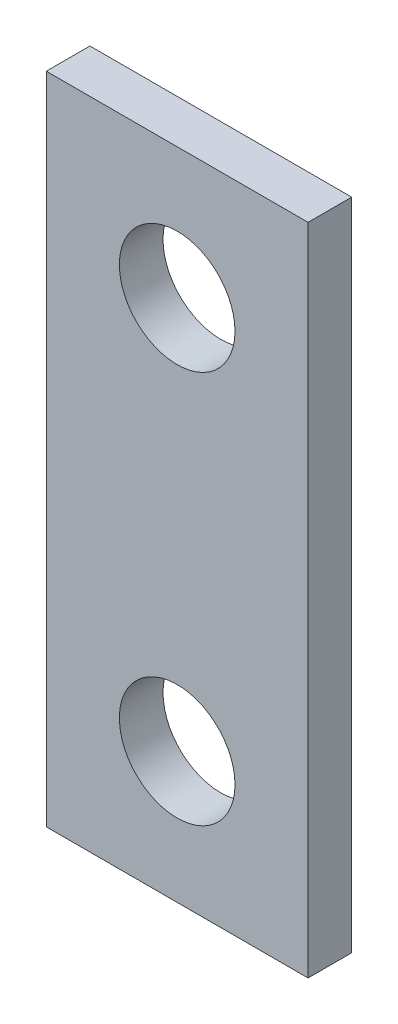
SolidWorks part; units mm, degrees
material "AISI 1045 钢，冷拔"
ref_plane "前视基准面" through (0, 0, 0) normal (0, 0, 1) x (1, 0, 0)
ref_plane "上视基准面" through (0, 0, 0) normal (0, 1, 0) x (1, 0, 0)
ref_plane "右视基准面" through (0, 0, 0) normal (1, 0, 0) x (0, 0, -1)
sketch "草图1" plane through (0, 0, 0) normal (0, 0, 1) x (1, 0, 0)
  line L1 (-6, -15) -> (6, -15)
  line L2 (-6, -15) -> (-6, 15)
  line L3 (-6, 15) -> (6, 15)
  line L4 (6, -15) -> (6, 15)
  line L5 (-6, -15) -> (6, 15) construction
  line L6 (-6, 15) -> (6, -15) construction
  point P0 (0, 0)
  dimension "D1" = 30
  dimension "D2" = 12
extrude "凸台-拉伸1" add sketch "草图1" along normal blind 2
hole_wizard "M5 间隙孔1" positions "草图3" profile "草图2" hole size "M5" standard "GB" end condition up to next
sketch "草图3" plane through (0, 0, 2) normal (0, 0, 1) x (1, 0, 0)
  line L0 (-6, -15) -> (6, -15) construction
  point P0 (0, -9)
  point P2 (0, 9)
  dimension "D1" = 18
  dimension "D2" = 6
sketch "草图2" plane through (0, -9, 2) normal (1, 0, 0) x (0, -1, 0)
  line L0 (0, 0) -> (0, 2)
  line L1 (0, 2) -> (2.65, 2)
  line L2 (2.65, 2) -> (2.65, 0)
  line L5 (2.65, 0) -> (0, 0)
  line L11 (0, -6.35) -> (0, 107.95) construction
  dimension "通孔孔直径" = 5.3
  dimension "通孔孔深度" = 2
